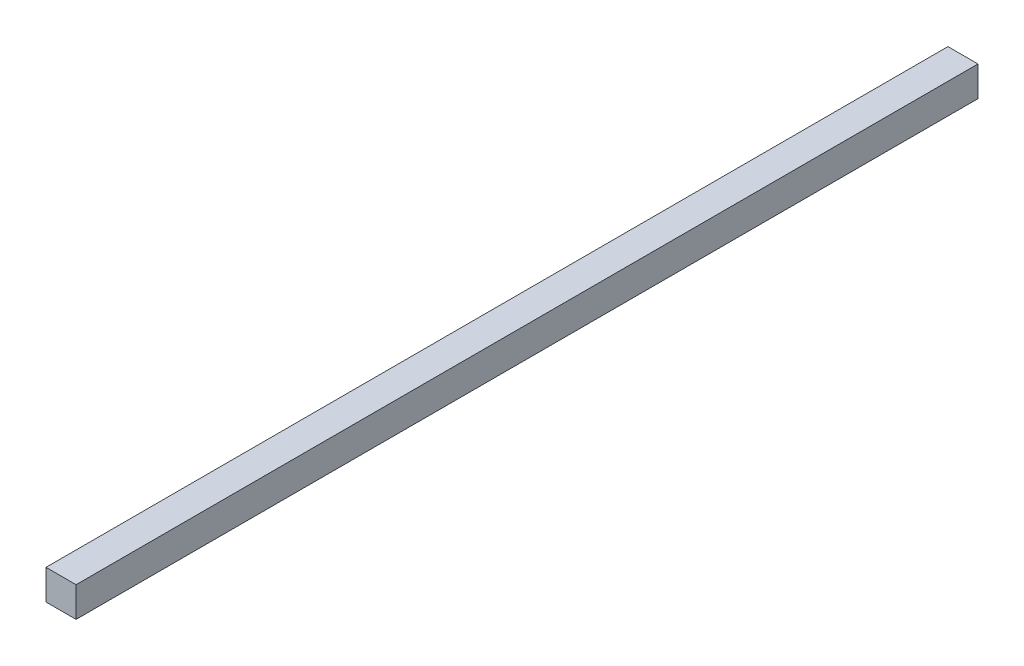
SolidWorks part; units mm, degrees
ref_plane "Plan de face" through (0, 0, 0) normal (0, 0, 1) x (1, 0, 0)
ref_plane "Plan de dessus" through (0, 0, 0) normal (0, 1, 0) x (1, 0, 0)
ref_plane "Plan de droite" through (0, 0, 0) normal (1, 0, 0) x (0, 0, -1)
sketch "Esquisse1" plane through (0, 0, 0) normal (0, 0, 1) x (1, 0, 0)
  line L1 (0, 0) -> (-200, 0)
  line L2 (0, 0) -> (0, 200)
  line L3 (0, 200) -> (-200, 200)
  line L4 (-200, 0) -> (-200, 200)
  dimension "D1" = 200
  dimension "D2" = 200
extrude "Boss.-Extru.1" add sketch "Esquisse1" against normal blind 6000
